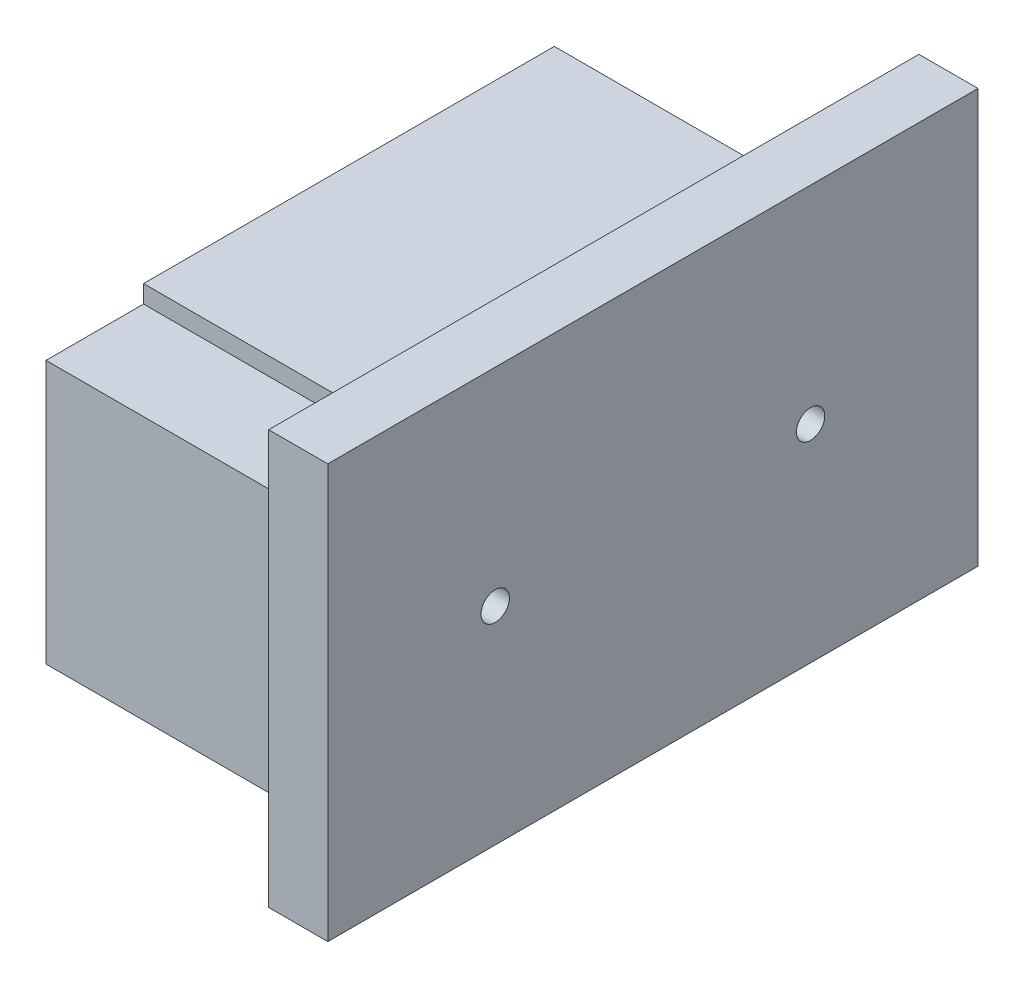
SolidWorks part; units mm, degrees
material "Pure Lead"
ref_plane "Front Plane" through (0, 0, 0) normal (0, 0, 1) x (1, 0, 0)
ref_plane "Top Plane" through (0, 0, 0) normal (0, 1, 0) x (1, 0, 0)
ref_plane "Right Plane" through (0, 0, 0) normal (1, 0, 0) x (0, 0, -1)
other "Lead Shot"
sketch "Sketch1" plane through (0, 0, 0) normal (0, 1, 0) x (1, 0, 0)
  line L1 (-22, -47) -> (22, -47)
  line L2 (-22, -47) -> (-22, 47)
  line L3 (-22, 47) -> (22, 47)
  line L4 (22, -47) -> (22, 47)
  line L5 (-22, -47) -> (22, 47) construction
  line L6 (-22, 47) -> (22, -47) construction
  point P0 (0, 0)
  dimension "D1" = 44
  dimension "D2" = 94
extrude "Boss-Extrude1" add sketch "Sketch1" along normal blind 47.5
sketch "Sketch2" plane through (22, 0, 0) normal (1, 0, 0) x (0, 0, -1)
  line L0 (-47, 47.5) -> (-47, 0) construction
  line L2 (-47, 47.5) -> (47, 47.5) construction
  circle A0 centre (-25, 24.5) radius 19
  circle A1 centre (28.35, 24.5) radius 19
  dimension "D2" = 38
  dimension "D1" = 53.35
  dimension "D3" = 22
  dimension "D4" = 23
extrude "Cut-Extrude1" cut sketch "Sketch2" against normal through all
sketch "Sketch3" plane through (22, 0, 0) normal (1, 0, 0) x (0, 0, -1)
  line L1 (47, 47.5) -> (39, 47.5)
  line L2 (47, 47.5) -> (47, 38.5)
  line L3 (47, 38.5) -> (39, 38.5)
  line L4 (39, 47.5) -> (39, 38.5)
  line L5 (-47, 47.5) -> (-30.5, 47.5)
  line L6 (-47, 47.5) -> (-47, 44.5)
  line L7 (-47, 44.5) -> (-30.5, 44.5)
  line L8 (-30.5, 47.5) -> (-30.5, 44.5)
  line L9 (47, 0) -> (45, 0)
  line L10 (47, 0) -> (47, 3)
  line L11 (47, 3) -> (45, 3)
  line L12 (45, 0) -> (45, 3)
  dimension "D1" = 3
  dimension "D2" = 8
  dimension "D3" = 16.5
  dimension "D4" = 9
  dimension "D5" = 3
  dimension "D6" = 2
extrude "Cut-Extrude2" cut sketch "Sketch3" against normal through all
sketch "Sketch4" plane through (22, 0, 0) normal (1, 0, 0) x (0, 0, -1)
  line L0 (-25, 24.5) -> (28.35, 24.5) construction
  line L2 (-53.325, -10.5) -> (56.675, -10.5)
  line L3 (-53.325, -10.5) -> (-53.325, 59.5)
  line L4 (-53.325, 59.5) -> (56.675, 59.5)
  line L5 (56.675, -10.5) -> (56.675, 59.5)
  line L6 (-53.325, -10.5) -> (56.675, 59.5) construction
  line L7 (-53.325, 59.5) -> (56.675, -10.5) construction
  line L9 (-47, 0) -> (45, 0)
  line L10 (45, 0) -> (45, 3)
  line L11 (45, 3) -> (47, 3)
  line L12 (47, 3) -> (47, 20.8699)
  line L13 (39, 40.2346) -> (39, 47.5)
  line L14 (39, 47.5) -> (-30.5, 47.5)
  line L15 (-30.5, 47.5) -> (-30.5, 44.5)
  line L16 (-30.5, 44.5) -> (-47, 44.5)
  line L17 (-47, 44.5) -> (-47, 0)
  line L18 (-47, 0) -> (45, 0)
  line L19 (45, 0) -> (45, 3)
  line L20 (45, 3) -> (47, 3)
  line L21 (47, 3) -> (47, 20.8699)
  line L22 (39, 40.2346) -> (39, 47.5)
  line L23 (39, 47.5) -> (-30.5, 47.5)
  line L24 (-30.5, 47.5) -> (-30.5, 44.5)
  line L25 (-30.5, 44.5) -> (-47, 44.5)
  line L26 (-47, 44.5) -> (-47, 0)
  circle A0 centre (-25, 24.5) radius 19 construction
  arc A1 (39, 40.2346) -> (47, 20.8699) centre (28.35, 24.5) ccw
  arc A2 (39, 40.2346) -> (47, 20.8699) centre (28.35, 24.5) ccw
  circle A3 centre (-25, 24.5) radius 19
  point P12 (1.675, 24.5)
  circle M13 centre (-25, 24.5) radius 19
  line M14 (-47, 0) -> (45, 0)
  line M15 (45, 0) -> (45, 3)
  line M16 (45, 3) -> (47, 3)
  line M17 (47, 3) -> (47, 20.8699)
  arc M18 (47, 20.8699) -> (39, 40.2346) centre (28.35, 24.5) cw
  line M19 (39, 40.2346) -> (39, 47.5)
  line M20 (39, 47.5) -> (-30.5, 47.5)
  line M21 (-30.5, 47.5) -> (-30.5, 44.5)
  line M22 (-30.5, 44.5) -> (-47, 44.5)
  line M23 (-47, 44.5) -> (-47, 0)
  dimension "D2" = 110
  dimension "D3" = 70
  dimension "D1" = 0
extrude "Boss-Extrude2" add sketch "Sketch4" along normal blind 10 separate body contours L2 L5 L4 L3 M14 M23 M22 M21 M20 M19 M18 M17 M16 M15 | M13 | M23 M14 M15 M16 M17 M18 M19 M20 M21 M22 M13
sketch "Sketch5" plane through (32, 0, 0) normal (1, 0, 0) x (0, 0, -1)
  circle A0 centre (-25, 24.5) radius 2.4
  circle A1 centre (28.35, 24.5) radius 2.4
  dimension "D1" = 4.8
extrude "Cut-Extrude3" cut sketch "Sketch5" against normal through all
